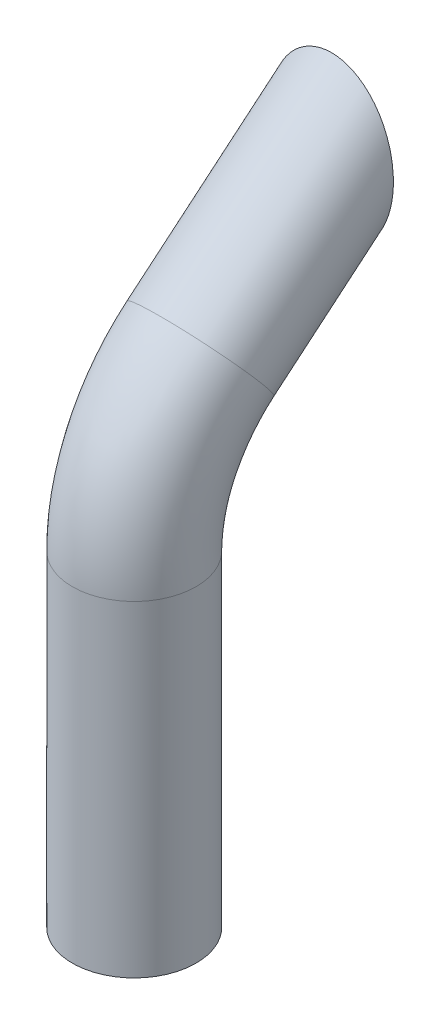
SolidWorks part; units mm, degrees
ref_plane "Front Plane" through (0, 0, 0) normal (0, 0, 1) x (1, 0, 0)
ref_plane "Top Plane" through (0, 0, 0) normal (0, 1, 0) x (1, 0, 0)
ref_plane "Right Plane" through (0, 0, 0) normal (1, 0, 0) x (0, 0, -1)
sketch "Sketch1" plane through (0, 0, 0) normal (1, 0, 0) x (0, 0, -1)
  line L0 (0, 0) -> (-82.7576, -69.4418)
  line L1 (-114.9067, -138.3858) -> (-114.9067, -296.4181)
  arc A0 (-114.9067, -138.3858) -> (-82.7576, -69.4418) centre (-24.9067, -138.3858) cw
  point P6 (-114.9067, -96.4181)
  dimension "D4" = 90
  dimension "D1" = 150
  dimension "D2" = 200
  dimension "D3" = 130
ref_plane "Plane1" through (0, 0, 0) normal (0, -0.6428, 0.766) x (1, 0, 0)
sketch "Sketch2" plane through (0, 0, 0) normal (0, -0.6428, 0.766) x (1, 0, 0)
  circle A0 centre (0, 0) radius 30
  dimension "D1" = 60
sweep "Sweep-Thin1" add profiles "Sketch2" path "Sketch1" parameters "D1"=3
sketch "Sketch3" plane through (0, 0, 0) normal (1, 0, 0) x (0, 0, -1)
  line L1 (-19.2836, 22.9813) -> (58.7893, 22.9813)
  line L2 (-19.2836, 22.9813) -> (-19.2836, -79.4814)
  line L3 (-19.2836, -79.4814) -> (58.7893, -79.4814)
  line L4 (58.7893, 22.9813) -> (58.7893, -79.4814)
extrude "Cut-Extrude1" cut sketch "Sketch3" against normal mid plane 258 contours L1 L4 L3 L2
